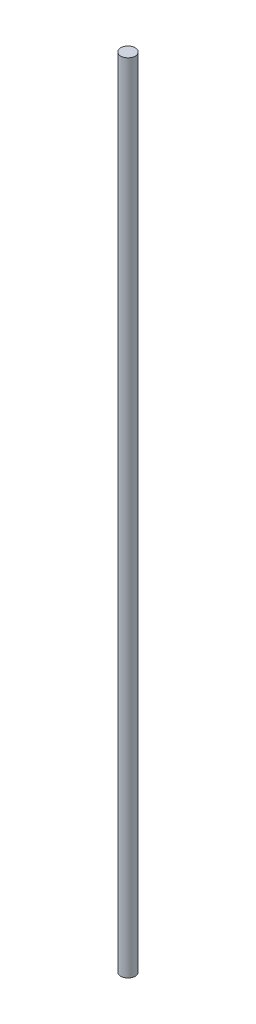
SolidWorks part; units mm, degrees
ref_plane "Спереди" through (0, 0, 0) normal (0, 0, 1) x (1, 0, 0)
ref_plane "Сверху" through (0, 0, 0) normal (0, 1, 0) x (1, 0, 0)
ref_plane "Справа" through (0, 0, 0) normal (1, 0, 0) x (0, 0, -1)
sketch "Эскиз1" plane through (0, 0, 0) normal (0, 1, 0) x (1, 0, 0)
  circle A0 centre (0, 0) radius 0.1
  dimension "D1" = 0.2
extrude "Бобышка-Вытянуть1" add sketch "Эскиз1" along normal blind 11
